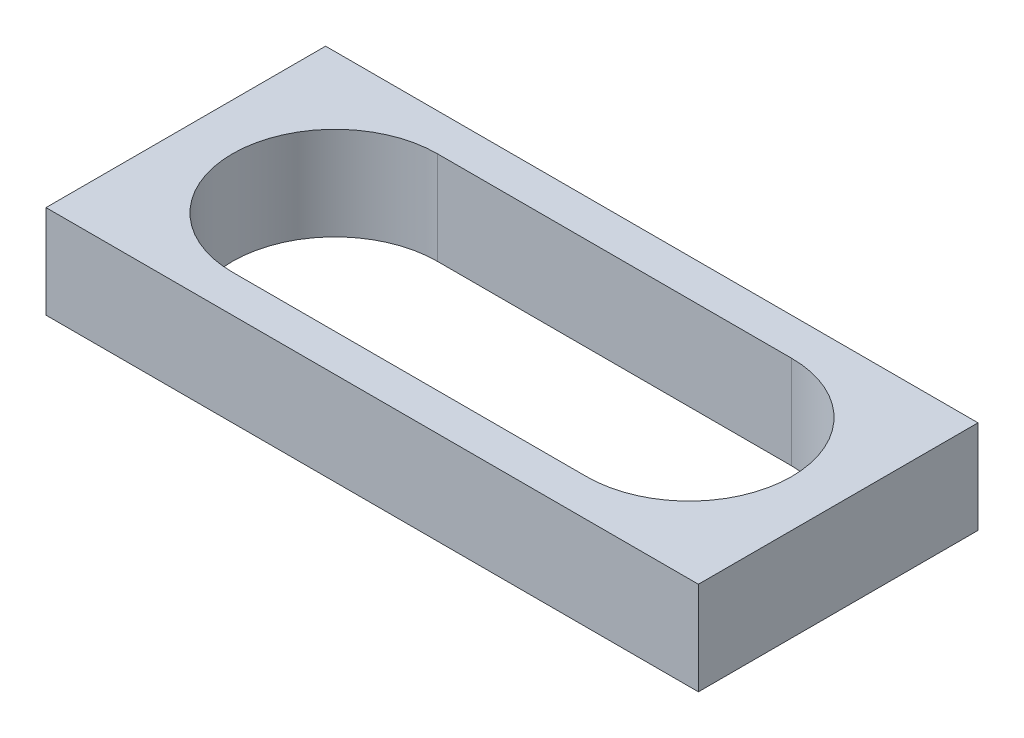
SolidWorks part; units mm, degrees
ref_plane "Front Plane" through (0, 0, 0) normal (0, 0, 1) x (1, 0, 0)
ref_plane "Top Plane" through (0, 0, 0) normal (0, 1, 0) x (1, 0, 0)
ref_plane "Right Plane" through (0, 0, 0) normal (1, 0, 0) x (0, 0, -1)
sketch "Sketch1" plane through (0, 0, 0) normal (0, 1, 0) x (1, 0, 0)
  line L0 (-12.065, 0) -> (12.065, 0) construction
  line L1 (-22.225, -9.525) -> (22.225, -9.525)
  line L2 (-22.225, -9.525) -> (-22.225, 9.525)
  line L3 (-22.225, 9.525) -> (22.225, 9.525)
  line L4 (22.225, -9.525) -> (22.225, 9.525)
  line L5 (-22.225, -9.525) -> (22.225, 9.525) construction
  line L6 (-22.225, 9.525) -> (22.225, -9.525) construction
  line L7 (-12.065, 6.985) -> (12.065, 6.985)
  line L8 (-12.065, -6.985) -> (12.065, -6.985)
  arc A0 (-12.065, 6.985) -> (-12.065, -6.985) centre (-12.065, 0) ccw
  arc A1 (12.065, -6.985) -> (12.065, 6.985) centre (12.065, 0) ccw
  point P0 (0, 0)
  point P8 (0, 0)
  dimension "D1" = 44.45
  dimension "D2" = 19.05
  dimension "D3" = 2.54
  dimension "D4" = 10.16
extrude "Boss-Extrude1" add sketch "Sketch1" along normal blind 6.35
equation "\"screw-bed-layer-length\"= 1.75in'Clamp left-to-right is barely under."
equation "\"screw-bed-layer-width\"= .75in'Clamp top-to-bottom is just over."
equation "\"material-thickness\"= .25in"
equation "\"D1@Sketch1\" = \"screw-bed-layer-length\""
equation "\"D2@Sketch1\"=\"screw-bed-layer-width\""
equation "\"D1@Boss-Extrude1\"= \"material-thickness\""
equation "\"slot-flat-edge-inset\"= .1in"
equation "\"D3@Sketch1\"=\"slot-flat-edge-inset\""
equation "\"slot-center-entpoint-to-layer-short-edge\"= .4in"
equation "\"D4@Sketch1\"=\"slot-center-entpoint-to-layer-short-edge\""
